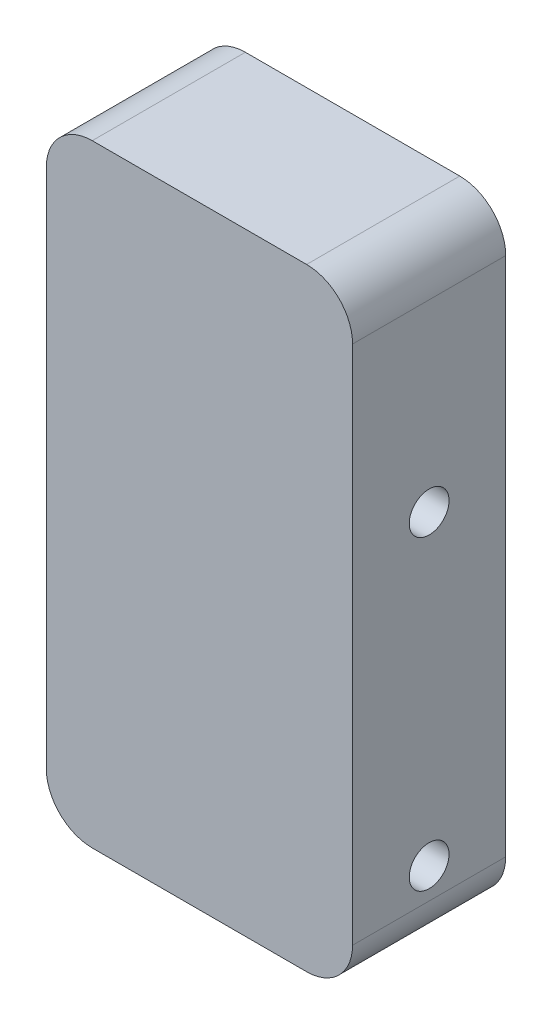
SolidWorks part; units mm, degrees
material "5052-H34"
ref_plane "正面" through (0, 0, 0) normal (0, 0, 1) x (1, 0, 0)
ref_plane "平面" through (0, 0, 0) normal (0, 1, 0) x (1, 0, 0)
ref_plane "右側面" through (0, 0, 0) normal (1, 0, 0) x (0, 0, -1)
sketch "ｽｹｯﾁ1" plane through (0, 0, 0) normal (0, 0, 1) x (1, 0, 0)
  line L1 (10, 20) -> (-10, 20)
  line L2 (10, 20) -> (10, -20)
  line L3 (10, -20) -> (-10, -20)
  line L4 (-10, 20) -> (-10, -20)
  line L5 (10, 20) -> (-10, -20) construction
  line L6 (10, -20) -> (-10, 20) construction
  line L7 (0, 0) -> (10, 0) construction
  point P0 (0, 0)
  dimension "D3" = 20
  dimension "D4" = 40
extrude "ﾎﾞｽ - 押し出し1" add sketch "ｽｹｯﾁ1" along normal blind 10
fillet "ﾌｨﾚｯﾄ1" radius 3 4 edges at (-10, 20, 5) (-10, -20, 5) (10, -20, 5) (10, 20, 5)
sketch "ｽｹｯﾁ2" plane through (10, 0, 0) normal (1, 0, 0) x (0, 0, -1)
  line L0 (-5, 20) -> (-5, -20) construction
  line L1 (-10, 20) -> (0, 20) construction
  line L2 (0, -20) -> (-10, -20) construction
  circle A0 centre (-5, -15) radius 1.3
  circle A1 centre (-5, 5) radius 1.3
  dimension "D1" = 20
  dimension "D2" = 2.6
  dimension "D3" = 5
extrude "ｶｯﾄ - 押し出し1" cut sketch "ｽｹｯﾁ2" against normal blind 15
